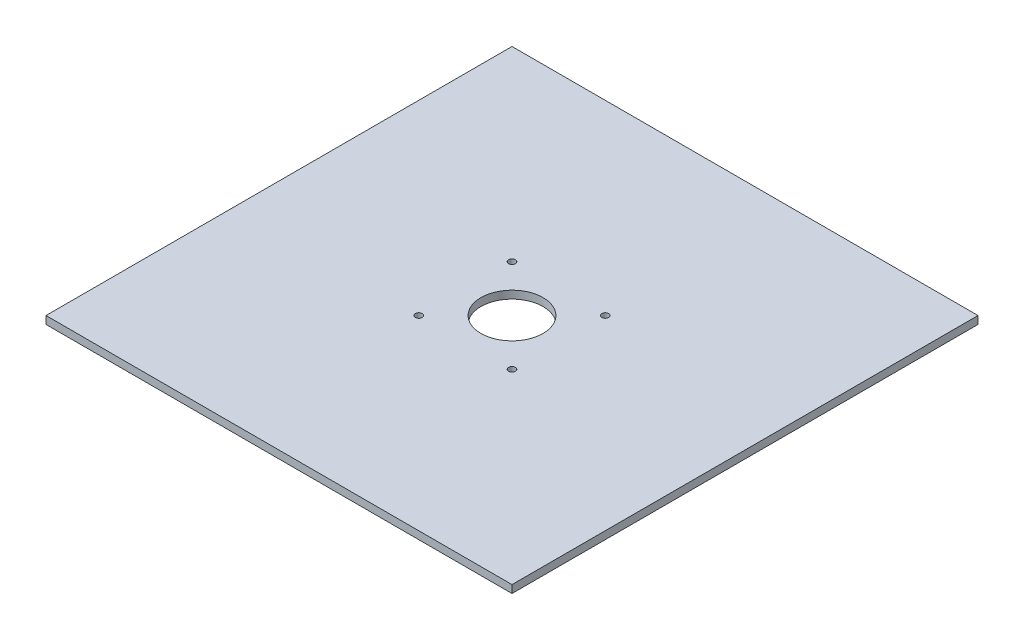
SolidWorks part; units mm, degrees
ref_plane "Front Plane" through (0, 0, 0) normal (0, 0, 1) x (1, 0, 0)
ref_plane "Top Plane" through (0, 0, 0) normal (0, 1, 0) x (1, 0, 0)
ref_plane "Right Plane" through (0, 0, 0) normal (1, 0, 0) x (0, 0, -1)
sketch "Sketch1" plane through (0, 0, 0) normal (0, 1, 0) x (1, 0, 0)
  line L1 (-150, -150) -> (150, -150)
  line L2 (-150, -150) -> (-150, 150)
  line L3 (-150, 150) -> (150, 150)
  line L4 (150, -150) -> (150, 150)
  line L5 (-150, -150) -> (150, 150) construction
  line L6 (-150, 150) -> (150, -150) construction
  line L7 (-30, -30) -> (30, -30) construction
  line L8 (-30, -30) -> (-30, 30) construction
  line L9 (-30, 30) -> (30, 30) construction
  line L10 (30, -30) -> (30, 30) construction
  line L11 (-30, -30) -> (30, 30) construction
  line L12 (-30, 30) -> (30, -30) construction
  circle A0 centre (0, 0) radius 20
  circle A1 centre (-30, 30) radius 2.2
  circle A2 centre (30, 30) radius 2.2
  circle A3 centre (30, -30) radius 2.2
  circle A4 centre (-30, -30) radius 2.2
  point P0 (0, 0)
  dimension "D3" = 60
  dimension "D4" = 2
  dimension "D1" = 300
  dimension "D2" = 300
  dimension "D5" = 2
extrude "Boss-Extrude1" add sketch "Sketch1" along normal blind 5
